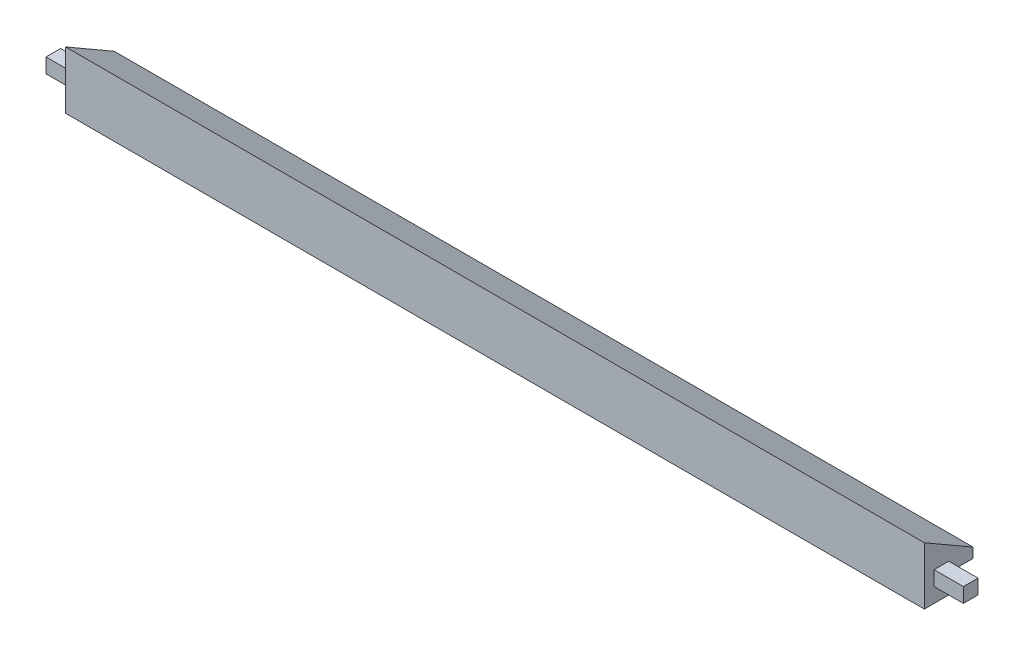
SolidWorks part; units mm, degrees
ref_plane "Front Plane" through (0, 0, 0) normal (0, 0, 1) x (1, 0, 0)
ref_plane "Top Plane" through (0, 0, 0) normal (0, 1, 0) x (1, 0, 0)
ref_plane "Right Plane" through (0, 0, 0) normal (1, 0, 0) x (0, 0, -1)
sketch "Sketch1" plane through (0, 0, 0) normal (1, 0, 0) x (0, 0, -1)
  line L1 (-1.4021, -1.5073) -> (3.5979, -1.5073)
  line L2 (3.5979, -1.5073) -> (3.5979, 1.4927)
  line L5 (-1.4021, -1.5073) -> (-1.4021, 4.3816)
  line L6 (-1.4021, 4.3816) -> (3.5979, 1.4927)
extrude "Boss-Extrude1" add sketch "Sketch1" along normal blind 88
sketch "Sketch2" plane through (0, 0, 0) normal (-1, 0, 0) x (0, 0, 1)
  line L1 (-3.5979, -1.5073) -> (-1.5979, -1.5073)
  line L2 (-3.5979, -1.5073) -> (-3.5979, 0.4927)
  line L3 (-3.5979, 0.4927) -> (-1.5979, 0.4927)
  line L4 (-1.5979, -1.5073) -> (-1.5979, 0.4927)
extrude "Cut-Extrude1" cut sketch "Sketch2" against normal blind 88
sketch "Sketch3" plane through (0, 0, 0) normal (-1, 0, 0) x (0, 0, 1)
  line L0 (1.4021, -1.5073) -> (1.4021, -0.0073) construction
  line L1 (1.4021, -0.0073) -> (0.4021, -0.0073) construction
  line L3 (0.4021, -0.0073) -> (-1.0979, -0.0073)
  line L4 (0.4021, -0.0073) -> (0.4021, 1.4927)
  line L5 (0.4021, 1.4927) -> (-1.0979, 1.4927)
  line L6 (-1.0979, -0.0073) -> (-1.0979, 1.4927)
extrude "Boss-Extrude2" add sketch "Sketch3" along normal blind 3
sketch "Sketch4" plane through (88, 0, 0) normal (1, 0, 0) x (0, 0, -1)
  line L0 (-1.4021, -1.5073) -> (-1.4021, -0.0073) construction
  line L1 (-1.4021, -0.0073) -> (-0.4021, -0.0073) construction
  line L3 (-0.4021, -0.0073) -> (1.0979, -0.0073)
  line L4 (-0.4021, -0.0073) -> (-0.4021, 1.4927)
  line L5 (-0.4021, 1.4927) -> (1.0979, 1.4927)
  line L6 (1.0979, -0.0073) -> (1.0979, 1.4927)
extrude "Boss-Extrude3" add sketch "Sketch4" along normal blind 3
